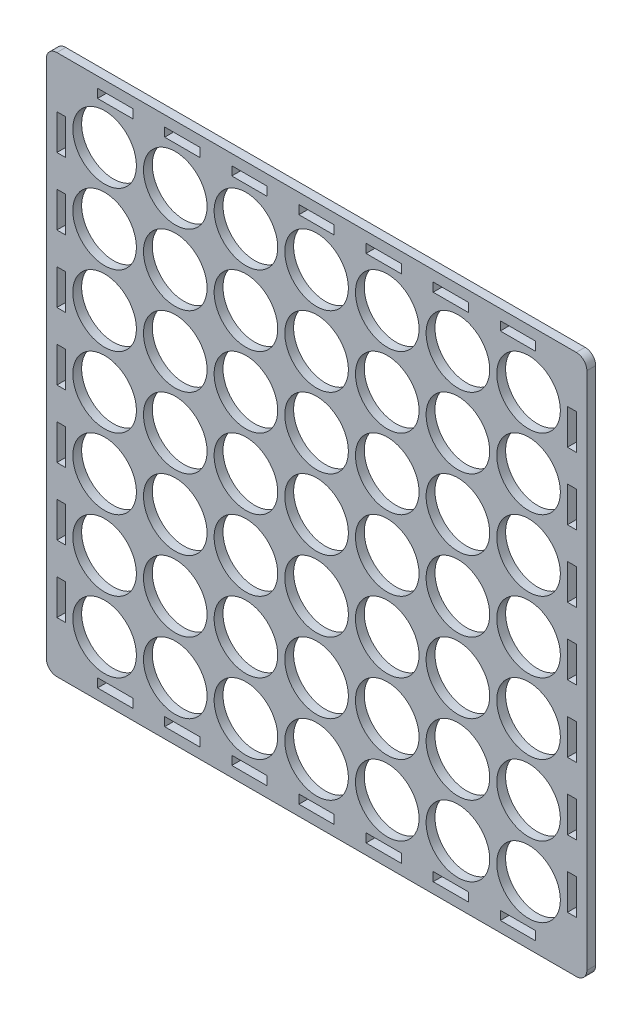
SolidWorks part; units mm, degrees
material "Beech"
ref_plane "Front" through (0, 0, 0) normal (0, 0, 1) x (1, 0, 0)
ref_plane "Top" through (0, 0, 0) normal (0, 1, 0) x (1, 0, 0)
ref_plane "Right" through (0, 0, 0) normal (1, 0, 0) x (0, 0, -1)
sketch "Sketch1" plane through (0, 0, 0) normal (0, 0, 1) x (1, 0, 0)
  line L0 (0, 14.1468) -> (0, -17.5978) construction
  line L1 (-76.5, -76.5) -> (76.5, -76.5)
  line L2 (-76.5, -76.5) -> (-76.5, 76.5)
  line L3 (-76.5, 76.5) -> (76.5, 76.5)
  line L4 (76.5, -76.5) -> (76.5, 76.5)
  line L5 (-76.5, -76.5) -> (76.5, 76.5) construction
  line L6 (-76.5, 76.5) -> (76.5, -76.5) construction
  line L7 (-73.5, 52) -> (-71, 52)
  line L8 (-73.5, 52) -> (-73.5, 62)
  line L9 (-73.5, 62) -> (-71, 62)
  line L10 (-71, 52) -> (-71, 62)
  line L11 (-73.5, 52) -> (-71, 62) construction
  line L12 (-73.5, 62) -> (-71, 52) construction
  line L13 (-21.7287, 0) -> (19.2748, 0) construction
  line L14 (-73.5, 33) -> (-73.5, 43)
  line L15 (-73.5, 33) -> (-71, 33)
  line L16 (-71, 33) -> (-71, 43)
  line L17 (-73.5, 43) -> (-71, 43)
  line L18 (-73.5, 14) -> (-73.5, 24)
  line L19 (-73.5, 14) -> (-71, 14)
  line L20 (-71, 14) -> (-71, 24)
  line L21 (-73.5, 24) -> (-71, 24)
  line L22 (-73.5, -5) -> (-73.5, 5)
  line L23 (-73.5, -5) -> (-71, -5)
  line L24 (-71, -5) -> (-71, 5)
  line L25 (-73.5, 5) -> (-71, 5)
  line L26 (-73.5, -24) -> (-73.5, -14)
  line L27 (-73.5, -24) -> (-71, -24)
  line L28 (-71, -24) -> (-71, -14)
  line L29 (-73.5, -14) -> (-71, -14)
  line L30 (-73.5, -43) -> (-73.5, -33)
  line L31 (-73.5, -43) -> (-71, -43)
  line L32 (-71, -43) -> (-71, -33)
  line L33 (-73.5, -33) -> (-71, -33)
  line L34 (-73.5, -62) -> (-73.5, -52)
  line L35 (-73.5, -62) -> (-71, -62)
  line L36 (-71, -62) -> (-71, -52)
  line L37 (-73.5, -52) -> (-71, -52)
  line L70 (73.5, -24) -> (71, -24)
  line L71 (71, -24) -> (71, -14)
  line L72 (73.5, -14) -> (71, -14)
  line L73 (73.5, -24) -> (73.5, -14)
  line L74 (73.5, -43) -> (71, -43)
  line L75 (71, -43) -> (71, -33)
  line L76 (73.5, -33) -> (71, -33)
  line L77 (73.5, -43) -> (73.5, -33)
  line L78 (73.5, -62) -> (71, -62)
  line L79 (71, -62) -> (71, -52)
  line L80 (73.5, -52) -> (71, -52)
  line L81 (73.5, -62) -> (73.5, -52)
  line L82 (73.5, -5) -> (71, -5)
  line L83 (71, -5) -> (71, 5)
  line L84 (73.5, 5) -> (71, 5)
  line L85 (73.5, -5) -> (73.5, 5)
  line L86 (73.5, 14) -> (71, 14)
  line L87 (71, 14) -> (71, 24)
  line L88 (73.5, 24) -> (71, 24)
  line L89 (73.5, 14) -> (73.5, 24)
  line L90 (73.5, 33) -> (71, 33)
  line L91 (71, 33) -> (71, 43)
  line L92 (73.5, 43) -> (71, 43)
  line L93 (73.5, 33) -> (73.5, 43)
  line L94 (73.5, 62) -> (71, 62)
  line L95 (71, 52) -> (71, 62)
  line L96 (73.5, 52) -> (71, 52)
  line L97 (73.5, 52) -> (73.5, 62)
  line L98 (-62, -73.5) -> (-52, -73.5)
  line L99 (-62, 71) -> (-52, 71)
  line L100 (-62, 71) -> (-62, 73.5)
  line L101 (-62, 73.5) -> (-52, 73.5)
  line L102 (-52, 71) -> (-52, 73.5)
  line L103 (-62, 71) -> (-52, 73.5) construction
  line L104 (-62, 73.5) -> (-52, 71) construction
  line L105 (-52, -71) -> (-52, -73.5)
  line L106 (-62, -71) -> (-52, -71)
  line L107 (-62, -71) -> (-62, -73.5)
  line L108 (-43, 71) -> (-43, 73.5)
  line L109 (-43, 71) -> (-33, 71)
  line L110 (-33, 71) -> (-33, 73.5)
  line L111 (-43, 73.5) -> (-33, 73.5)
  line L112 (-43, -73.5) -> (-33, -73.5)
  line L113 (-33, -71) -> (-33, -73.5)
  line L114 (-43, -71) -> (-33, -71)
  line L115 (-43, -71) -> (-43, -73.5)
  line L116 (-24, 71) -> (-24, 73.5)
  line L117 (-24, 71) -> (-14, 71)
  line L118 (-14, 71) -> (-14, 73.5)
  line L119 (-24, 73.5) -> (-14, 73.5)
  line L120 (-24, -73.5) -> (-14, -73.5)
  line L121 (-14, -71) -> (-14, -73.5)
  line L122 (-24, -71) -> (-14, -71)
  line L123 (-24, -71) -> (-24, -73.5)
  line L124 (-5, 71) -> (-5, 73.5)
  line L125 (-5, 71) -> (5, 71)
  line L126 (5, 71) -> (5, 73.5)
  line L127 (-5, 73.5) -> (5, 73.5)
  line L128 (-5, -73.5) -> (5, -73.5)
  line L129 (5, -71) -> (5, -73.5)
  line L130 (-5, -71) -> (5, -71)
  line L131 (-5, -71) -> (-5, -73.5)
  line L132 (14, 71) -> (14, 73.5)
  line L133 (14, 71) -> (24, 71)
  line L134 (24, 71) -> (24, 73.5)
  line L135 (14, 73.5) -> (24, 73.5)
  line L136 (14, -73.5) -> (24, -73.5)
  line L137 (24, -71) -> (24, -73.5)
  line L138 (14, -71) -> (24, -71)
  line L139 (14, -71) -> (14, -73.5)
  line L140 (33, 71) -> (33, 73.5)
  line L141 (33, 71) -> (43, 71)
  line L142 (43, 71) -> (43, 73.5)
  line L143 (33, 73.5) -> (43, 73.5)
  line L144 (33, -73.5) -> (43, -73.5)
  line L145 (43, -71) -> (43, -73.5)
  line L146 (33, -71) -> (43, -71)
  line L147 (33, -71) -> (33, -73.5)
  line L148 (52, 71) -> (52, 73.5)
  line L149 (52, 71) -> (62, 71)
  line L150 (62, 71) -> (62, 73.5)
  line L151 (52, 73.5) -> (62, 73.5)
  line L152 (52, -73.5) -> (62, -73.5)
  line L153 (62, -71) -> (62, -73.5)
  line L154 (52, -71) -> (62, -71)
  line L155 (52, -71) -> (52, -73.5)
  point P0 (0, 0)
  point P6 (-72.25, 57)
  point P67 (-57, 72.25)
  dimension "D1" = 153
  dimension "D2" = 153
  dimension "D3" = 10
  dimension "D4" = 2.5
  dimension "D5" = 3
  dimension "D6" = 14.5
  dimension "D8" = 9
  dimension "D9" = 3
  dimension "D10" = 14.5
  dimension "D12" = 9
  dimension "D7" = 7
  dimension "D11" = 7
extrude "Boss-Extrude1" add sketch "Sketch1" along normal blind 2.5 contours L1 L4 L3 L2 L155 L154 L153 L152 L147 L146 L145 L144 L139 L138 L137 L136 L131 L130 L129 L128 L123 L122 L121 L120 L115 L114 L113 L112 L107 L106 L105 L98 L102 L99 L100 L101 L97 L96 L95 L94 L93
sketch "Sketch2" plane through (0, 0, 2.5) normal (0, 0, 1) x (1, 0, 0)
  line L0 (52, 71) -> (62, 71) construction
  line L1 (71, 52) -> (71, 62) construction
  circle A0 centre (60, 60) radius 9
  circle A1 centre (40, 60) radius 9
  circle A2 centre (20, 60) radius 9
  circle A3 centre (0, 60) radius 9
  circle A4 centre (-20, 60) radius 9
  circle A5 centre (-40, 60) radius 9
  circle A6 centre (-60, 60) radius 9
  circle A7 centre (40, 40) radius 9
  circle A8 centre (20, 40) radius 9
  circle A9 centre (0, 40) radius 9
  circle A10 centre (-20, 40) radius 9
  circle A11 centre (-40, 40) radius 9
  circle A12 centre (-60, 40) radius 9
  circle A13 centre (40, 20) radius 9
  circle A14 centre (20, 20) radius 9
  circle A15 centre (0, 20) radius 9
  circle A16 centre (-20, 20) radius 9
  circle A17 centre (-40, 20) radius 9
  circle A18 centre (-60, 20) radius 9
  circle A19 centre (40, 0) radius 9
  circle A20 centre (20, 0) radius 9
  circle A21 centre (0, 0) radius 9
  circle A22 centre (-20, 0) radius 9
  circle A23 centre (-40, 0) radius 9
  circle A24 centre (-60, 0) radius 9
  circle A25 centre (40, -20) radius 9
  circle A26 centre (20, -20) radius 9
  circle A27 centre (0, -20) radius 9
  circle A28 centre (-20, -20) radius 9
  circle A29 centre (-40, -20) radius 9
  circle A30 centre (-60, -20) radius 9
  circle A31 centre (40, -40) radius 9
  circle A32 centre (20, -40) radius 9
  circle A33 centre (0, -40) radius 9
  circle A34 centre (-20, -40) radius 9
  circle A35 centre (-40, -40) radius 9
  circle A36 centre (-60, -40) radius 9
  circle A37 centre (40, -60) radius 9
  circle A38 centre (20, -60) radius 9
  circle A39 centre (0, -60) radius 9
  circle A40 centre (-20, -60) radius 9
  circle A41 centre (-40, -60) radius 9
  circle A42 centre (-60, -60) radius 9
  circle A43 centre (60, 40) radius 9
  circle A44 centre (60, 20) radius 9
  circle A45 centre (60, 0) radius 9
  circle A46 centre (60, -20) radius 9
  circle A47 centre (60, -40) radius 9
  circle A48 centre (60, -60) radius 9
  dimension "D1" = 18
  dimension "D2" = 11
  dimension "D3" = 11
  dimension "D6" = 20
  dimension "D7" = 20
  dimension "D4" = 7
  dimension "D5" = 7
extrude "Cut-Extrude1" cut sketch "Sketch2" against normal up to next (2.5 mm away)
fillet "Fillet1" radius 3 4 edges at (76.5, -76.5, 1.25) (-76.5, -76.5, 1.25) (76.5, 76.5, 1.25) (-76.5, 76.5, 1.25)
